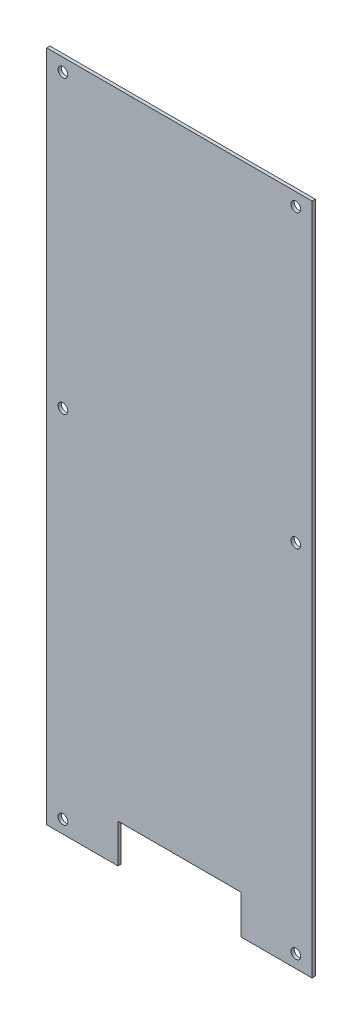
SolidWorks part; units mm, degrees
ref_plane "Front Plane" through (0, 0, 0) normal (0, 0, 1) x (1, 0, 0)
ref_plane "Top Plane" through (0, 0, 0) normal (0, 1, 0) x (1, 0, 0)
ref_plane "Right Plane" through (0, 0, 0) normal (1, 0, 0) x (0, 0, -1)
sketch "Sketch1" plane through (0, 0, 0) normal (0, 0, 1) x (1, 0, 0)
  line L1 (41, -104) -> (-41, -104)
  line L2 (41, -104) -> (41, 104)
  line L3 (41, 104) -> (-41, 104)
  line L4 (-41, -104) -> (-41, 104)
  line L5 (41, -104) -> (-41, 104) construction
  line L6 (41, 104) -> (-41, -104) construction
  point P0 (0, 0)
  dimension "D1" = 82
  dimension "D2" = 208
extrude "Boss-Extrude1" add sketch "Sketch1" along normal blind 1
hole_wizard "Ø3.0 (3) Diameter Hole1" positions "Sketch3" profile "Sketch2" hole size "Ø3.0" standard "ANSI Metric"
sketch "Sketch3" plane through (0, 0, 1) normal (0, 0, 1) x (1, 0, 0)
  line L6 (-41, -104) -> (41, -104) construction
  point P0 (-36, 10)
  point P2 (36, 10)
  point P15 (36, -100)
  point P17 (-36, -100)
  point P36 (-36, 100)
  point P40 (36, 100)
  dimension "D2" = 4
  dimension "D4" = 4
sketch "Sketch2" plane through (-36, 10, 1) normal (1, 0, 0) x (0, -1, 0)
  line L0 (0, 0) -> (0, 1)
  line L1 (0, 1) -> (1.5, 1)
  line L2 (1.5, 1) -> (1.5, 0)
  line L5 (1.5, 0) -> (0, 0)
  line L10 (0, 1) -> (-1.5, 1) construction
  line L11 (0, -6.35) -> (0, 107.95) construction
  dimension "Hole Dia." = 3
  dimension "Hole Depth" = 1
  dimension "Drill Angle" = 180
sketch "Sketch4" plane through (0, 0, 1) normal (0, 0, 1) x (1, 0, 0)
  line L0 (-41, -104) -> (41, -104) construction
  line L1 (-19, -92) -> (19, -92)
  line L2 (-19, -92) -> (-19, -104)
  line L3 (-19, -104) -> (19, -104)
  line L4 (19, -92) -> (19, -104)
  line L5 (-41, 104) -> (-41, -104) construction
  line L6 (41, -104) -> (41, 104) construction
  dimension "D1" = 12
  dimension "D2" = 22
  dimension "D3" = 22
extrude "Cut-Extrude1" cut sketch "Sketch4" against normal blind 10
